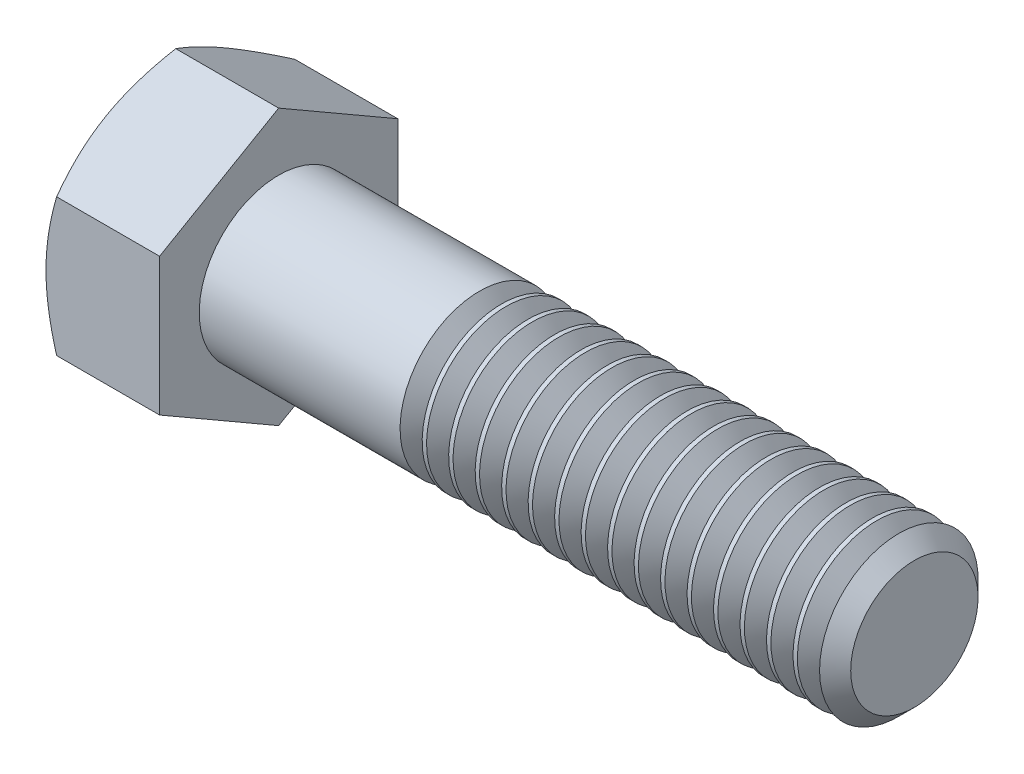
SolidWorks part; units mm, degrees
extrude "BaseHead" add sketch "Sketch1" along normal blind 6.8072
sketch "Sketch1" plane through (0, 0, 0) normal (1, 0, 0) x (0, 0, -1)
  line L0 (7.1374, 4.1208) -> (7.1374, -4.1208)
  line L1 (-7.1374, 4.1208) -> (-7.1374, -4.1208)
  line L2 (7.1374, -4.1208) -> (0, -8.2416)
  line L3 (0, -8.2416) -> (-7.1374, -4.1208)
  line L4 (7.1374, 4.1208) -> (0, 8.2416)
  line L5 (0, 8.2416) -> (-7.1374, 4.1208)
  dimension "Width_flats" = 14.2748
  dimension "D2" = 120
  dimension "D3" = 7.1374
  dimension "D4" = 7.1374
  dimension "D5" = 7.1374
ref_plane "Plane1" through (0, 0, 0) normal (0, 0, 1) x (1, 0, 0)
ref_plane "Plane2" through (0, 0, 0) normal (0, 1, 0) x (1, 0, 0)
ref_plane "Plane3" through (0, 0, 0) normal (1, 0, 0) x (0, 0, -1)
other "Configuration Table"
sketch "BodySke" plane through (0, 0, 0) normal (0, 0, 1) x (1, 0, 0)
  line L0 (0, 4.1208) -> (0, -4.1208) construction
  line L1 (0, 0) -> (44.9072, 0)
  line L2 (0, 0) -> (0, 4.7625)
  line L3 (0, 4.7625) -> (43.961, 4.7625)
  line L4 (44.9072, 0) -> (44.9072, 3.8163)
  line L5 (6.8072, 8.2416) -> (6.8072, 4.1208) construction
  line L6 (44.9072, 3.8163) -> (43.961, 4.7625)
  line L7 (0, 0) -> (96.52, 0) construction
  line L8 (44.9072, -3.8163) -> (43.961, -4.7625) construction
  line L9 (0, -4.7625) -> (43.961, -4.7625) construction
  line L10 (8.3947, 15.24) -> (8.3947, -2.54) construction
  line L11 (19.5072, 15.24) -> (19.5072, -2.54) construction
  line L12 (6.8072, 4.1208) -> (6.8072, -4.1208) construction
  dimension "Diameter" = 9.525
  dimension "Advance" = 1.5875
revolve "BaseBody" add sketch "BodySke" angle 360 about L7
cosmetic thread "ThreadCosmetic" [suppressed] parameters "Thread_length"=25.4, "Thread_minor"=7.6327
sketch "Sketch3" plane through (0, 0, 0) normal (0, 0, 1) x (1, 0, 0)
  line L0 (0, 7.1374) -> (4.3037, 14.5916)
  line L1 (0, 8.2416) -> (0, 4.1208) construction
  line L2 (4.3037, 14.5916) -> (4.3037, 20.9416)
  line L3 (4.3037, 20.9416) -> (-12.7, 20.9416)
  line L4 (-12.7, 20.9416) -> (-12.7, 7.1374)
  line L5 (-12.7, 7.1374) -> (0, 7.1374)
  line L6 (0, 0) -> (99.06, 0) construction
  line L7 (6.8072, 8.2416) -> (0, 8.2416) construction
  dimension "D1" = 7.1374
  dimension "D2" = 6.35
  dimension "D3" = 12.7
  dimension "D4" = 6.35
  dimension "Head_ch_ang" = 30
revolve "HeadChamfer" cut sketch "Sketch3" angle 360 about L6
fillet "HeadFillet" [suppressed] radius 0.762
sketch "ThdSchSke" plane through (0, 0, 0) normal (0, 0, 1) x (1, 0, 0)
  line L0 (19.5072, -3.8163) -> (18.8447, -4.7625)
  line L1 (19.5072, -3.8163) -> (20.1697, -4.7625)
  line L2 (20.1697, -4.7625) -> (20.1697, -5.9531)
  line L3 (-3.175, 0) -> (5.1513, 0) construction
  line L5 (20.1697, -5.9531) -> (18.8447, -5.9531)
  line L6 (18.8447, -5.9531) -> (18.8447, -4.7625)
  dimension "Thread_minor" = 7.6327
  dimension "Diameter" = 9.525
  dimension "Start" = 19.5072
revolve "ThreadSchematic" cut sketch "ThdSchSke" angle 360 about L3
pattern_linear "ThdSchPat" count 16 spacing 1.5875 along (1, 0, 0) of "ThreadSchematic"
equation "\"D3@Sketch1\" = \"Width_flats@Sketch1\" / 2"
equation "\"D4@Sketch1\" = \"D3@Sketch1\""
equation "\"D5@Sketch1\" = \"D4@Sketch1\""
equation "\"Thread_minor@ThreadCosmetic\" = \"Minor_dia@BodySke\""
equation "\"D1@Sketch3\" = \"Width_flats@Sketch1\" / 2"
equation "\"Thread_length@ThreadCosmetic\" = ((sgn( (\"Length@BodySke\" - \"Advance@BodySke\" ) - \"Thread_nom@BodySke\" )-1)*( (\"Length@BodySke\" - \"Advance@BodySke\" ) - \"Thread_nom@BodySke\" ))/-2+ \"Thread_nom@BodySke\""
equation "\"Thread_minor@ThdSchSke\" = \"Minor_dia@BodySke\""
equation "\"Diameter@ThdSchSke\" = \"Diameter@BodySke\""
equation "\"Overcut@ThdSchSke\" = \"Diameter@BodySke\" * 1.25"
equation "\"Start@ThdSchSke\" = \"Head_ht@BaseHead\" + \"Length@BodySke\" - \"Thread_length@ThreadCosmetic\"  '---Non-countersunk---"
equation "\"Num_threads@ThdSchPat\" = int( \"Thread_length@ThreadCosmetic\" / \"Advance@BodySke\" + 0.999 )  + 1"
equation "\"Advance@ThdSchPat\" = \"Thread_length@ThreadCosmetic\" /  (\"Num_threads@ThdSchPat\" - 1) 'relax it"
equation "\"Num_threads@ThdSchPat\" = \"Num_threads@ThdSchPat\" - sgn( \"Num_threads@ThdSchPat\" - 1) '---chamfered tips only---"
